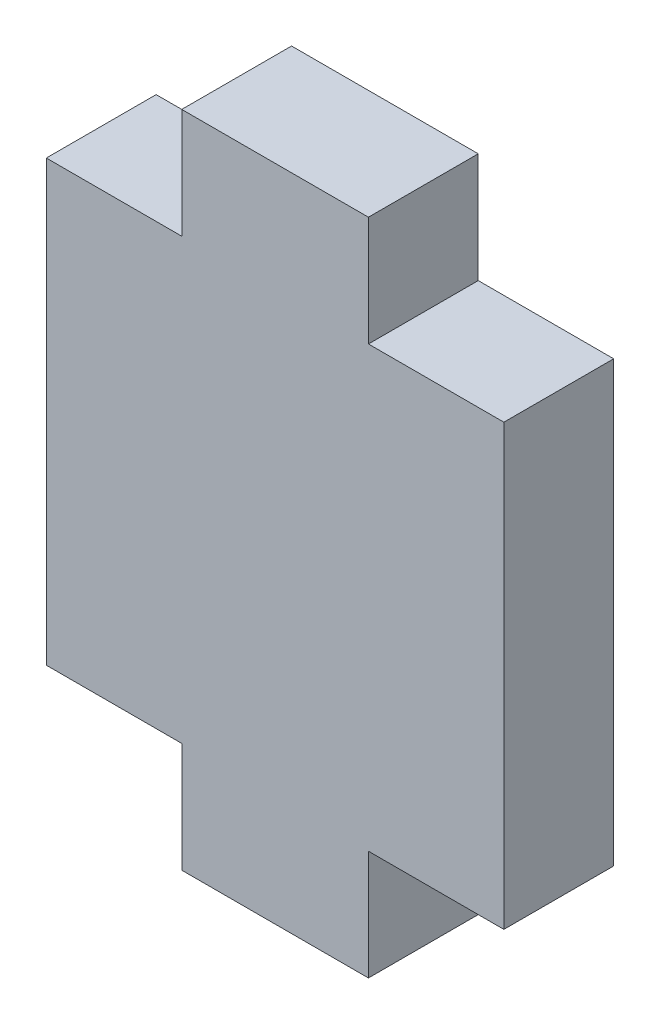
SolidWorks part; units mm, degrees
ref_plane "Plan de face" through (0, 0, 0) normal (0, 0, 1) x (1, 0, 0)
ref_plane "Plan de dessus" through (0, 0, 0) normal (0, 1, 0) x (1, 0, 0)
ref_plane "Plan de droite" through (0, 0, 0) normal (1, 0, 0) x (0, 0, -1)
sketch "Esquisse1" plane through (0, 0, 0) normal (0, 0, 1) x (1, 0, 0)
  line L0 (0, 0) -> (0, 6)
  line L1 (0, 6) -> (-7.4, 6)
  line L2 (-7.4, 6) -> (-7.4, 30)
  line L3 (-7.4, 30) -> (0, 30)
  line L4 (0, 30) -> (0, 36)
  line L5 (0, 36) -> (10.2, 36)
  line L6 (10.2, 36) -> (10.2, 30)
  line L7 (10.2, 30) -> (17.6, 30)
  line L8 (17.6, 30) -> (17.6, 6)
  line L9 (17.6, 6) -> (10.2, 6)
  line L10 (10.2, 6) -> (10.2, 0)
  line L11 (10.2, 0) -> (0, 0)
  line L12 (5.1, 0) -> (5.1, 36) construction
  dimension "D1" = 6
  dimension "D2" = 10.2
  dimension "D3" = 10.2
  dimension "D4" = 24
  dimension "D5" = 24
  dimension "D6" = 6
  dimension "D7" = 25
extrude "Boss.-Extru.1" add sketch "Esquisse1" along normal blind 6
